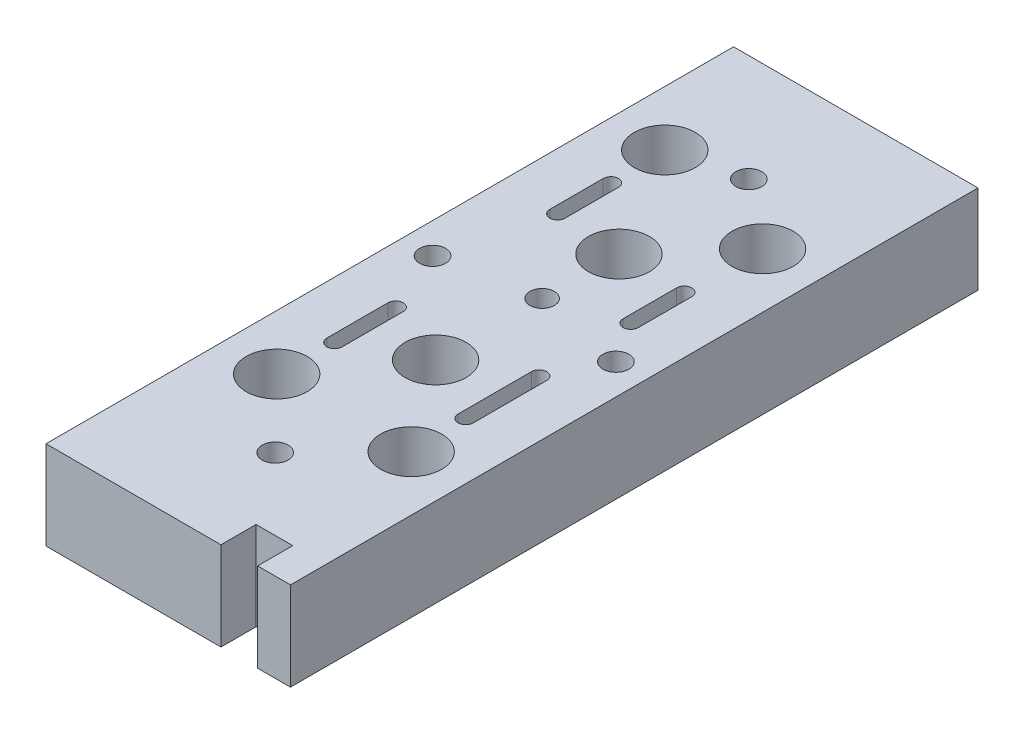
SolidWorks part; units mm, degrees
material "Plain Carbon Steel"
ref_plane "Front Plane" through (0, 0, 0) normal (0, 0, 1) x (1, 0, 0)
ref_plane "Top Plane" through (0, 0, 0) normal (0, 1, 0) x (1, 0, 0)
ref_plane "Right Plane" through (0, 0, 0) normal (1, 0, 0) x (0, 0, -1)
sketch "Sketch1" plane through (0, 0, 0) normal (0, 1, 0) x (1, 0, 0)
  line L1 (-40, -112.5) -> (40, -112.5)
  line L2 (-40, -112.5) -> (-40, 112.5)
  line L3 (-40, 112.5) -> (40, 112.5)
  line L4 (40, -112.5) -> (40, 112.5)
  line L5 (-40, -112.5) -> (40, 112.5) construction
  line L6 (-40, 112.5) -> (40, -112.5) construction
  point P0 (0, 0)
  dimension "D1" = 225
  dimension "D2" = 80
extrude "Boss-Extrude1" add sketch "Sketch1" against normal blind 29
sketch "Sketch2" plane through (0, 0, 0) normal (0, 1, 0) x (1, 0, 0)
  line L0 (-19, 36.36) -> (-19, 53.86) construction
  line L1 (-24, 53.86) -> (-24, 36.36) construction
  line L2 (-19, -36.59) -> (-19, -16.59) construction
  line L3 (-24, -16.59) -> (-24, -36.59) construction
  line L4 (24, 17.36) -> (24, 34.86) construction
  line L5 (19, 34.86) -> (19, 17.36) construction
  line L8 (24, -36.64) -> (24, -12.64) construction
  line L9 (19, -12.64) -> (19, -36.64) construction
  line L11 (-19, 36.36) -> (-19, 53.86)
  line L14 (-24, 53.86) -> (-24, 36.36)
  line L15 (-19, -36.59) -> (-19, -16.59)
  line L16 (-24, -16.59) -> (-24, -36.59)
  line L17 (24, 17.36) -> (24, 34.86)
  line L20 (19, 34.86) -> (19, 17.36)
  line L21 (24, -36.64) -> (24, -12.64)
  line L23 (19, -12.64) -> (19, -36.64)
  arc A0 (-24, 36.36) -> (-19, 36.36) centre (-21.5, 36.36) ccw construction
  arc A1 (-19, 53.86) -> (-24, 53.86) centre (-21.5, 53.86) ccw construction
  arc A2 (-24, -36.59) -> (-19, -36.59) centre (-21.5, -36.59) ccw construction
  arc A3 (-19, -16.59) -> (-24, -16.59) centre (-21.5, -16.59) ccw construction
  arc A4 (19, 17.36) -> (24, 17.36) centre (21.5, 17.36) ccw construction
  arc A5 (24, 34.86) -> (19, 34.86) centre (21.5, 34.86) ccw construction
  arc A8 (19, -36.64) -> (24, -36.64) centre (21.5, -36.64) ccw construction
  arc A9 (24, -12.64) -> (19, -12.64) centre (21.5, -12.64) ccw construction
  arc A14 (-24, 36.36) -> (-19, 36.36) centre (-21.5, 36.36) ccw
  arc A15 (-19, 53.86) -> (-24, 53.86) centre (-21.5, 53.86) ccw
  arc A16 (-24, -36.59) -> (-19, -36.59) centre (-21.5, -36.59) ccw
  arc A17 (-19, -16.59) -> (-24, -16.59) centre (-21.5, -16.59) ccw
  arc A20 (19, 17.36) -> (24, 17.36) centre (21.5, 17.36) ccw
  arc A21 (24, 34.86) -> (19, 34.86) centre (21.5, 34.86) ccw
  arc A26 (19, -36.64) -> (24, -36.64) centre (21.5, -36.64) ccw
  arc A27 (24, -12.64) -> (19, -12.64) centre (21.5, -12.64) ccw
extrude "Cut-Extrude1" cut sketch "Sketch2" against normal up to next
sketch "Sketch4" plane through (0, 0, 0) normal (0, 1, 0) x (1, 0, 0)
  circle A0 centre (-22, 72) radius 10
  circle A1 centre (22, 60) radius 10
  circle A2 centre (0, 35) radius 10
  circle A3 centre (0, -25) radius 10
  circle A4 centre (22, -55) radius 10
  circle A5 centre (-22, -55) radius 10
  dimension "D1" = 20
extrude "Cut-Extrude2" cut sketch "Sketch4" against normal blind 17
sketch "Sketch5" plane through (0, -29, 0) normal (0, -1, 0) x (1, 0, 0)
  circle A0 centre (0, 100) radius 8.5
  circle A1 centre (0, -100) radius 8.5
  dimension "D1" = 17
extrude "Cut-Extrude3" cut sketch "Sketch5" against normal blind 5
sketch "Sketch6" plane through (0, 0, 0) normal (0, 1, 0) x (1, 0, 0)
  line L0 (-40, -112.5) -> (40, -112.5) construction
  line L1 (17.25, -112.5) -> (29.25, -112.5)
  line L2 (17.25, -112.5) -> (17.25, -101)
  line L3 (17.25, -101) -> (29.25, -101)
  line L4 (29.25, -112.5) -> (29.25, -101)
  line L5 (28.25, -102.5) -> (28.25, -115) construction
  line L6 (18.25, -115) -> (18.25, -102.5) construction
  line L7 (18.75, -102) -> (27.75, -102) construction
  point P8 (28.25, -108.75)
  point P11 (18.25, -108.75)
  dimension "D1" = 1
  dimension "D2" = 1
  dimension "D3" = 1
extrude "Cut-Extrude4" cut sketch "Sketch6" against normal up to next
hole_wizard "M10 Tapped Hole1" positions "Sketch9" profile "Sketch8" tap size "M10" standard "ISO" end condition through all
sketch "Sketch9" plane through (0, 0, 0) normal (0, 1, 0) x (1, 0, 0)
  point P0 (0, -77.5)
  point P2 (30, 4)
  point P4 (-30, 4)
  point P6 (0, 77.5)
  dimension "D1" = 77.5
  dimension "D2" = 77.5
  dimension "D3" = 4
  dimension "D4" = 30
  dimension "D5" = 30
sketch "Sketch8" plane through (0, 0, 77.5) normal (1, 0, 0) x (0, 0, 1)
  line L0 (0, 0) -> (0, 29)
  line L1 (0, 29) -> (4.25, 29)
  line L2 (4.25, 29) -> (4.25, 0)
  line L5 (4.25, 0) -> (0, 0)
  line L11 (0, -6.35) -> (0, 107.95) construction
  dimension "Thru Tap Drill Dia." = 8.5
  dimension "Thru Tap Drill Depth" = 29
cosmetic thread "Hole Thread1" parameters "D2"=10
cosmetic thread "Hole Thread2" parameters "D2"=10
cosmetic thread "Hole Thread3" parameters "D2"=10
cosmetic thread "Hole Thread4" parameters "D2"=10
sketch "Sketch10" plane through (0, 0, 0) normal (0, 1, 0) x (1, 0, 0)
  circle A0 centre (0, 9.86) radius 5 construction
  circle A1 centre (0, 9.86) radius 5 construction
  circle A2 centre (0, 9.86) radius 4
  dimension "D1" = 8
extrude "Cut-Extrude5" cut sketch "Sketch10" against normal up to next
